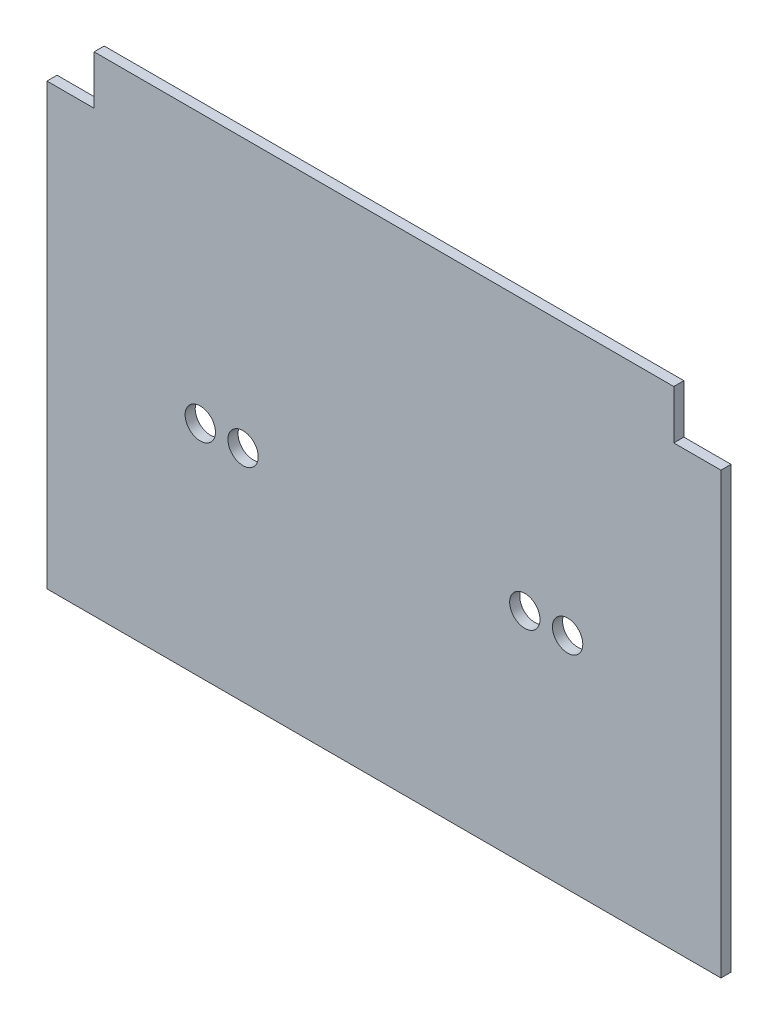
SolidWorks part; units mm, degrees
material "Pine"
ref_plane "Front Plane" through (0, 0, 0) normal (0, 0, 1) x (1, 0, 0)
ref_plane "Top Plane" through (0, 0, 0) normal (0, 1, 0) x (1, 0, 0)
ref_plane "Right Plane" through (0, 0, 0) normal (1, 0, 0) x (0, 0, -1)
sketch "Sketch1" plane through (0, 0, 0) normal (0, 0, 1) x (1, 0, 0)
  line L1 (-28.5714, 258.1048) -> (371.4286, 258.1048)
  line L2 (-28.5714, 258.1048) -> (-28.5714, -22.8952)
  line L3 (-28.5714, -22.8952) -> (371.4286, -22.8952)
  line L4 (371.4286, 258.1048) -> (371.4286, -22.8952)
  dimension "D1" = 281
  dimension "D2" = 400
extrude "Boss-Extrude1" add sketch "Sketch1" along normal blind 6
sketch "Sketch2" plane through (0, 0, 6) normal (0, 0, 1) x (1, 0, 0)
  line L1 (-28.5714, 258.1048) -> (-0.5714, 258.1048)
  line L2 (-28.5714, 258.1048) -> (-28.5714, 238.1048)
  line L3 (-28.5714, 238.1048) -> (-0.5714, 238.1048)
  line L4 (-0.5714, 258.1048) -> (-0.5714, 238.1048)
  line L5 (371.4286, 258.1048) -> (343.4286, 258.1048)
  line L6 (371.4286, 258.1048) -> (371.4286, 238.1048)
  line L7 (371.4286, 238.1048) -> (343.4286, 238.1048)
  line L8 (343.4286, 258.1048) -> (343.4286, 238.1048)
  dimension "D1" = 20
  dimension "D2" = 20
  dimension "D3" = 28
  dimension "D4" = 28
extrude "Cut-Extrude1" cut sketch "Sketch2" against normal blind 10
sketch "Sketch3" plane through (0, 0, 6) normal (0, 0, 1) x (1, 0, 0)
  line L0 (343.4286, 258.1048) -> (343.4286, 238.1048) construction
  line L1 (-0.5714, 258.1048) -> (343.4286, 258.1048)
  line L2 (-0.5714, 258.1048) -> (-0.5714, 267.1048)
  line L3 (-0.5714, 267.1048) -> (343.4286, 267.1048)
  line L4 (343.4286, 258.1048) -> (343.4286, 267.1048)
  dimension "D1" = 0
  dimension "D2" = 9
extrude "Boss-Extrude2" add sketch "Sketch3" against normal up to vertex (6 mm away)
sketch "Sketch4" plane through (0, 0, 6) normal (0, 0, 1) x (1, 0, 0)
  line L0 (-28.5714, -22.8952) -> (371.4286, -22.8952) construction
  line L1 (-28.5714, 238.1048) -> (-28.5714, -22.8952) construction
  line L2 (371.4286, -22.8952) -> (371.4286, 238.1048) construction
  circle A0 centre (62.4286, 107.6048) radius 9
  circle A1 centre (87.8286, 107.6048) radius 9
  circle A2 centre (255.0286, 107.6048) radius 9
  circle A3 centre (280.4286, 107.6048) radius 9
  dimension "D1" = 0
  dimension "D2" = 0
  dimension "D3" = 0
  dimension "D4" = 130.5
  dimension "D5" = 91
  dimension "D6" = 91
  dimension "D7" = 116.4
  dimension "D8" = 116.4
  dimension "D9" = 18
  dimension "D10" = 18
  dimension "D11" = 18
  dimension "D12" = 18
extrude "Cut-Extrude2" cut sketch "Sketch4" against normal blind 10
